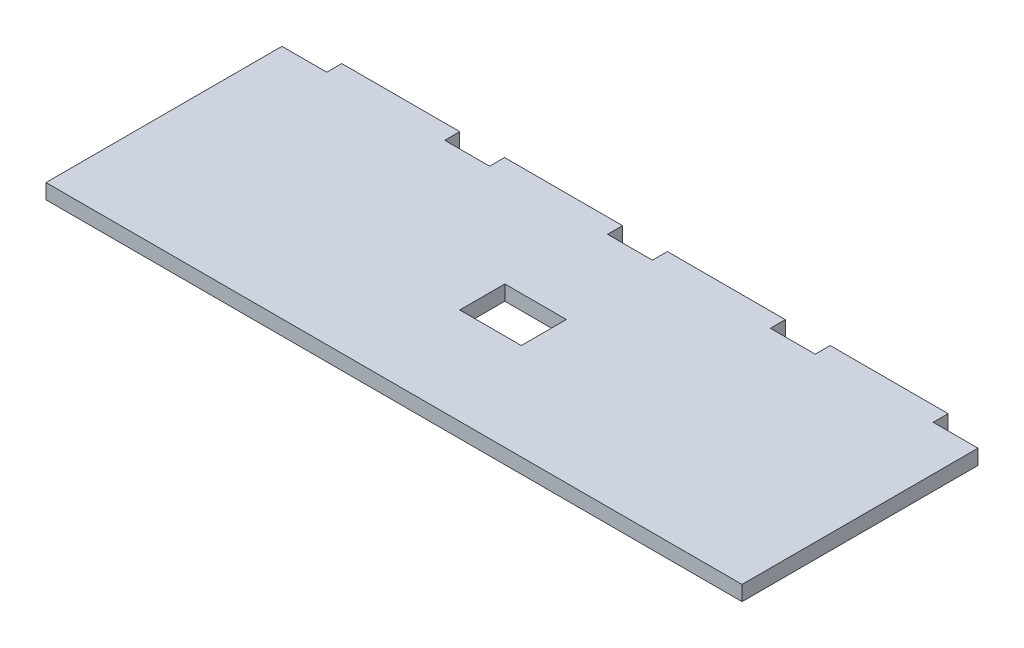
SolidWorks part; units mm, degrees
material "Beech"
ref_plane "Front Plane" through (0, 0, 0) normal (0, 0, 1) x (1, 0, 0)
ref_plane "Top Plane" through (0, 0, 0) normal (0, 1, 0) x (1, 0, 0)
ref_plane "Right Plane" through (0, 0, 0) normal (1, 0, 0) x (0, 0, -1)
sketch "Sketch1" plane through (0, 0, 0) normal (0, 1, 0) x (1, 0, 0)
  line L2 (0, 0) -> (0, -100)
  line L3 (0, -100) -> (295, -100)
  line L4 (295, 0) -> (295, -100)
  line L5 (134.45, -40) -> (160.55, -40)
  line L6 (134.45, -40) -> (134.45, -59.1)
  line L7 (134.45, -59.1) -> (160.55, -59.1)
  line L8 (160.55, -40) -> (160.55, -59.1)
  line L24 (0, 0) -> (19, 0)
  line L45 (19, 0) -> (19, 6.35)
  line L46 (19, 6.35) -> (69, 6.35)
  line L47 (69, 0) -> (69, 6.35)
  line L48 (88, 0) -> (88, 6.35)
  line L49 (88, 6.35) -> (138, 6.35)
  line L50 (138, 0) -> (138, 6.35)
  line L52 (157, 0) -> (157, 6.35)
  line L53 (157, 6.35) -> (207, 6.35)
  line L54 (207, 0) -> (207, 6.35)
  line L56 (226, 0) -> (226, 6.35)
  line L57 (226, 6.35) -> (276, 6.35)
  line L58 (276, 0) -> (276, 6.35)
  line L59 (69, 0) -> (88, 0)
  line L60 (207, 0) -> (226, 0)
  line L61 (276, 0) -> (295, 0)
  line L62 (138, 0) -> (157, 0)
  dimension "D1" = 295
  dimension "D2" = 100
  dimension "D3" = 40
  dimension "D4" = 19.1
  dimension "D5" = 134.45
  dimension "D6" = 6.35
  dimension "D7" = 50
  dimension "D8" = 19
  dimension "D9" = 4
  dimension "D11" = 26.1
  dimension "D10" = 19
extrude "Boss-Extrude1" add sketch "Sketch1" along normal blind 6.35
